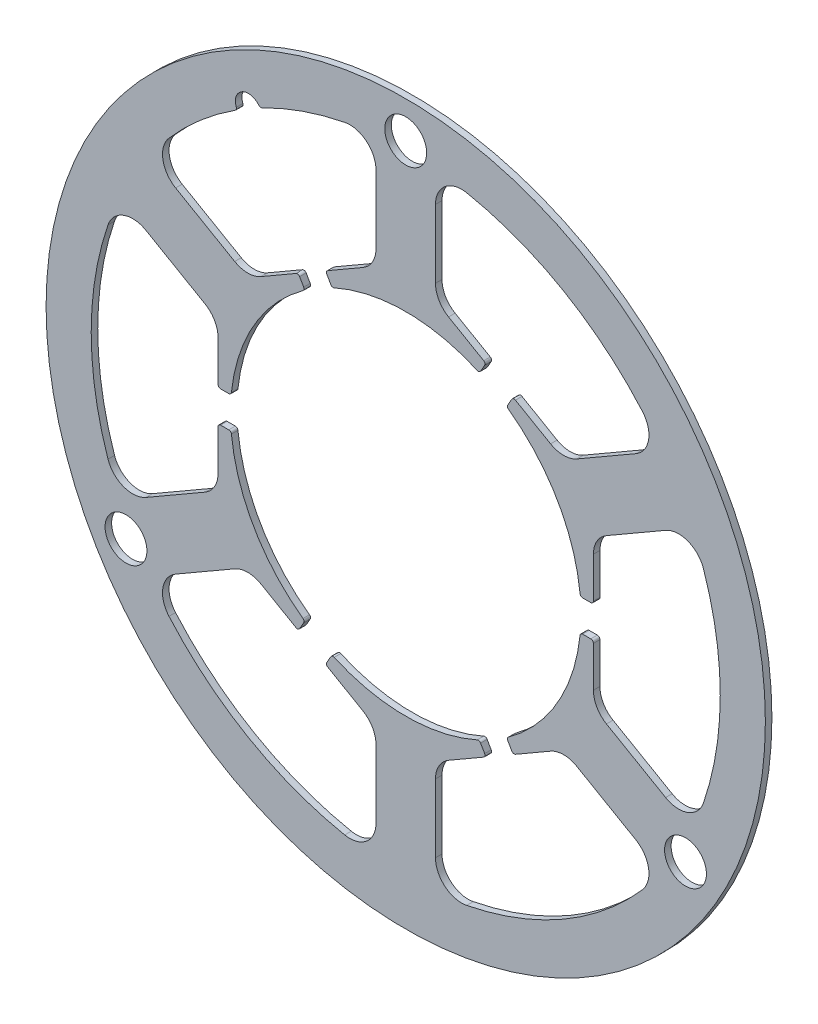
SolidWorks part; units mm, degrees
ref_plane "Ön Düzlem" through (0, 0, 0) normal (0, 0, 1) x (1, 0, 0)
ref_plane "Üst Düzlem" through (0, 0, 0) normal (0, 1, 0) x (1, 0, 0)
ref_plane "Sağ Düzlem" through (0, 0, 0) normal (1, 0, 0) x (0, 0, -1)
sketch "Çizim1" plane through (0, 0, 0) normal (0, 0, 1) x (1, 0, 0)
  line L0 (5.9626, 13.1275) -> (3.275, 14.6791)
  line L1 (3.275, -14.6791) -> (5.9626, -13.1275)
  line L2 (14.35, -4.5033) -> (14.35, -1.4)
  line L3 (11.075, 10.1758) -> (8.3874, 11.7275)
  line L4 (-3.275, 14.6791) -> (-5.9626, 13.1275)
  line L5 (-14.35, 4.5033) -> (-14.35, 1.4)
  line L6 (-11.075, -10.1758) -> (-8.3874, -11.7275)
  line L8 (8.3874, -11.7275) -> (11.075, -10.1758)
  line L9 (-5.9626, -13.1275) -> (-3.275, -14.6791)
  line L10 (-14.35, -1.4) -> (-14.35, -4.5033)
  line L11 (-2.275, 16.4112) -> (-2.275, 21.6316)
  line L12 (-8.1142, 11.6543) -> (-7.8031, 11.1154)
  line L13 (-6.0358, 12.8543) -> (-5.7246, 12.3154)
  line L14 (6.0358, 12.8543) -> (5.7246, 12.3154)
  line L15 (8.1142, 11.6543) -> (7.8031, 11.1154)
  line L16 (14.15, 1.2) -> (13.5277, 1.2)
  line L17 (14.15, -1.2) -> (13.5277, -1.2)
  line L18 (8.1142, -11.6543) -> (7.8031, -11.1154)
  line L19 (6.0358, -12.8543) -> (5.7246, -12.3154)
  line L20 (-6.0358, -12.8543) -> (-5.7246, -12.3154)
  line L21 (-8.1142, -11.6543) -> (-7.8031, -11.1154)
  line L22 (-14.15, -1.2) -> (-13.5277, -1.2)
  line L23 (-14.15, 1.2) -> (-13.5277, 1.2)
  line L24 (-8.3874, 11.7275) -> (-11.075, 10.1758)
  line L25 (14.35, 1.4) -> (14.35, 4.5033)
  line L26 (2.275, 16.4112) -> (2.275, 21.6316)
  line L27 (13.075, 10.1758) -> (17.596, 12.786)
  line L28 (15.35, 6.2354) -> (19.871, 8.8456)
  line L29 (15.35, -6.2354) -> (19.871, -8.8456)
  line L30 (13.075, -10.1758) -> (17.596, -12.786)
  line L31 (2.275, -16.4112) -> (2.275, -21.6316)
  line L32 (-2.275, -16.4112) -> (-2.275, -21.6316)
  line L33 (-13.075, -10.1758) -> (-17.596, -12.786)
  line L34 (-15.35, -6.2354) -> (-19.871, -8.8456)
  line L35 (-15.35, 6.2354) -> (-19.871, 8.8456)
  line L36 (-13.075, 10.1758) -> (-17.596, 12.786)
  circle A0 centre (0, 0) radius 27.5
  arc A1 (-4.6628, 23.5937) -> (-10.9904, 21.3919) centre (0, 0) ccw
  arc A3 (-7.859, 10.8534) -> (-13.3288, 1.3794) centre (0, 0) ccw
  arc A4 (5.4698, 12.2328) -> (-5.4698, 12.2328) centre (0, 0) ccw
  arc A7 (13.3288, 1.3794) -> (7.859, 10.8534) centre (0, 0) ccw
  arc A8 (7.859, -10.8534) -> (13.3288, -1.3794) centre (0, 0) ccw
  arc A10 (-5.4698, -12.2328) -> (5.4698, -12.2328) centre (0, 0) ccw
  arc A12 (-13.3288, -1.3794) -> (-7.859, -10.8534) centre (0, 0) ccw
  arc A14 (18.1013, 15.8349) -> (4.6628, 23.5937) centre (0, 0) ccw
  arc A15 (22.7641, -7.7588) -> (22.7641, 7.7588) centre (0, 0) ccw
  arc A16 (4.6628, -23.5937) -> (18.1013, -15.8349) centre (0, 0) ccw
  arc A17 (-18.1013, -15.8349) -> (-4.6628, -23.5937) centre (0, 0) ccw
  arc A18 (-22.7641, 7.7588) -> (-22.7641, -7.7588) centre (0, 0) ccw
  arc A19 (-15.35, 6.2354) -> (-14.35, 4.5033) centre (-16.35, 4.5033) cw
  arc A20 (-19.871, 8.8456) -> (-22.7641, 7.7588) centre (-20.871, 7.1136) ccw
  arc A21 (-15.35, -6.2354) -> (-14.35, -4.5033) centre (-16.35, -4.5033) ccw
  arc A22 (-19.871, -8.8456) -> (-22.7641, -7.7588) centre (-20.871, -7.1136) cw
  arc A23 (-13.075, -10.1758) -> (-11.075, -10.1758) centre (-12.075, -11.9078) cw
  arc A24 (-17.596, -12.786) -> (-18.1013, -15.8349) centre (-16.596, -14.5181) ccw
  arc A25 (-2.275, -16.4112) -> (-3.275, -14.6791) centre (-4.275, -16.4112) ccw
  arc A26 (-2.275, -21.6316) -> (-4.6628, -23.5937) centre (-4.275, -21.6316) cw
  arc A27 (2.275, -16.4112) -> (3.275, -14.6791) centre (4.275, -16.4112) cw
  arc A28 (2.275, -21.6316) -> (4.6628, -23.5937) centre (4.275, -21.6316) ccw
  arc A29 (13.075, -10.1758) -> (11.075, -10.1758) centre (12.075, -11.9078) ccw
  arc A30 (17.596, -12.786) -> (18.1013, -15.8349) centre (16.596, -14.5181) cw
  arc A31 (15.35, -6.2354) -> (14.35, -4.5033) centre (16.35, -4.5033) cw
  arc A32 (19.871, -8.8456) -> (22.7641, -7.7588) centre (20.871, -7.1136) ccw
  arc A33 (19.871, 8.8456) -> (22.7641, 7.7588) centre (20.871, 7.1136) cw
  arc A34 (15.35, 6.2354) -> (14.35, 4.5033) centre (16.35, 4.5033) ccw
  arc A35 (13.075, 10.1758) -> (11.075, 10.1758) centre (12.075, 11.9078) cw
  arc A36 (17.596, 12.786) -> (18.1013, 15.8349) centre (16.596, 14.5181) ccw
  arc A37 (2.275, 16.4112) -> (3.275, 14.6791) centre (4.275, 16.4112) ccw
  arc A38 (2.275, 21.6316) -> (4.6628, 23.5937) centre (4.275, 21.6316) cw
  arc A39 (-2.275, 16.4112) -> (-3.275, 14.6791) centre (-4.275, 16.4112) cw
  arc A40 (-13.075, 10.1758) -> (-11.075, 10.1758) centre (-12.075, 11.9078) ccw
  arc A41 (-17.596, 12.786) -> (-18.1013, 15.8349) centre (-16.596, 14.5181) cw
  arc A42 (-2.275, 21.6316) -> (-4.6628, 23.5937) centre (-4.275, 21.6316) ccw
  circle A43 centre (0, 24.7) radius 1.6
  circle A44 centre (21.3908, -12.35) radius 1.6
  circle A45 centre (-21.3908, -12.35) radius 1.6
  arc A46 (-11.239, 21.4461) -> (-12.9534, 20.4563) centre (-12.025, 20.8279) ccw
  arc A47 (-13.0307, 20.2139) -> (-18.1013, 15.8349) centre (0, 0) ccw
  arc A48 (-13.5277, 1.2) -> (-13.3288, 1.3794) centre (-13.5277, 1.4) ccw
  arc A49 (-14.35, 1.4) -> (-14.15, 1.2) centre (-14.15, 1.4) ccw
  arc A50 (-14.35, -1.4) -> (-14.15, -1.2) centre (-14.15, -1.4) cw
  arc A51 (-13.5277, -1.2) -> (-13.3288, -1.3794) centre (-13.5277, -1.4) cw
  arc A52 (-8.3874, -11.7275) -> (-8.1142, -11.6543) centre (-8.2874, -11.5543) ccw
  arc A53 (-7.8031, -11.1154) -> (-7.859, -10.8534) centre (-7.9763, -11.0154) ccw
  arc A54 (-5.9626, -13.1275) -> (-6.0358, -12.8543) centre (-5.8626, -12.9543) cw
  arc A55 (-5.7246, -12.3154) -> (-5.4698, -12.2328) centre (-5.5514, -12.4154) cw
  arc A56 (5.7246, -12.3154) -> (5.4698, -12.2328) centre (5.5514, -12.4154) ccw
  arc A57 (5.9626, -13.1275) -> (6.0358, -12.8543) centre (5.8626, -12.9543) ccw
  arc A58 (8.3874, -11.7275) -> (8.1142, -11.6543) centre (8.2874, -11.5543) cw
  arc A59 (7.8031, -11.1154) -> (7.859, -10.8534) centre (7.9763, -11.0154) cw
  arc A60 (14.35, -1.4) -> (14.15, -1.2) centre (14.15, -1.4) ccw
  arc A61 (13.5277, -1.2) -> (13.3288, -1.3794) centre (13.5277, -1.4) ccw
  arc A62 (13.5277, 1.2) -> (13.3288, 1.3794) centre (13.5277, 1.4) cw
  arc A63 (14.35, 1.4) -> (14.15, 1.2) centre (14.15, 1.4) cw
  arc A64 (7.8031, 11.1154) -> (7.859, 10.8534) centre (7.9763, 11.0154) ccw
  arc A65 (8.3874, 11.7275) -> (8.1142, 11.6543) centre (8.2874, 11.5543) ccw
  arc A66 (5.7246, 12.3154) -> (5.4698, 12.2328) centre (5.5514, 12.4154) cw
  arc A67 (6.0358, 12.8543) -> (5.9626, 13.1275) centre (5.8626, 12.9543) ccw
  arc A68 (-5.9626, 13.1275) -> (-6.0358, 12.8543) centre (-5.8626, 12.9543) ccw
  arc A69 (-5.7246, 12.3154) -> (-5.4698, 12.2328) centre (-5.5514, 12.4154) ccw
  arc A70 (-7.8031, 11.1154) -> (-7.859, 10.8534) centre (-7.9763, 11.0154) cw
  arc A71 (-8.3874, 11.7275) -> (-8.1142, 11.6543) centre (-8.2874, 11.5543) cw
  arc A72 (-12.9534, 20.4563) -> (-13.0307, 20.2139) centre (-13.1391, 20.382) cw
  arc A73 (-11.239, 21.4461) -> (-10.9904, 21.3919) centre (-11.0818, 21.5698) ccw
  point P3 (0, 0)
  point P5 (-14.35, 19.3252)
  point P11 (-6.0358, 12.8543)
  point P13 (-8.3874, 11.7275)
  point P14 (-7.859, 10.8534)
  point P15 (-5.4698, 12.2328)
  point P29 (0, 0)
  point P51 (0, 0)
  point P72 (0, 0)
  point P123 (0, 0)
  point P125 (-15.35, 18.5711)
  point P126 (0, 0)
  point P127 (0, 0)
  point P128 (0, 0)
  point P129 (0, 0)
  point P173 (-6.1358, 13.0275)
  point P176 (-5.6338, 12.1581)
  point P179 (-7.7123, 10.9581)
  point P182 (-8.2142, 11.8275)
  point P185 (-12.8804, 20.31)
  point P188 (0, 0)
  point P189 (-14.2997, 1.2)
  point P190 (-13.5277, -1.2)
  point P191 (-13.5277, 1.3794)
  point P192 (-14.15, 1.4)
  point P193 (-14.2997, 1.2)
  point P194 (8.1142, 11.6543)
  point P195 (7.8031, 11.1154)
  point P196 (7.859, 10.8534)
  dimension "D1" = 55
  dimension "D2" = 48.1
  dimension "D4" = 26.8
  dimension "D12" = 2
  dimension "D13" = 3.2
  dimension "D14" = 1.2
  dimension "D16" = 2
  dimension "D18" = 0.2
  dimension "D3" = 28.7
  dimension "D5" = 2.4
  dimension "D7" = 6
  dimension "D8" = 2.275
  dimension "D6" = 2.4
  dimension "D9" = 4.55
  dimension "D10" = 120
  dimension "D11" = 6
  dimension "D17" = 30
  dimension "D19" = 2.4
  dimension "D20" = 2.4
  dimension "D15" = 3
extrude "Yükseklik-Ekstrüzyon1" add sketch "Çizim1" along normal blind 0.5
